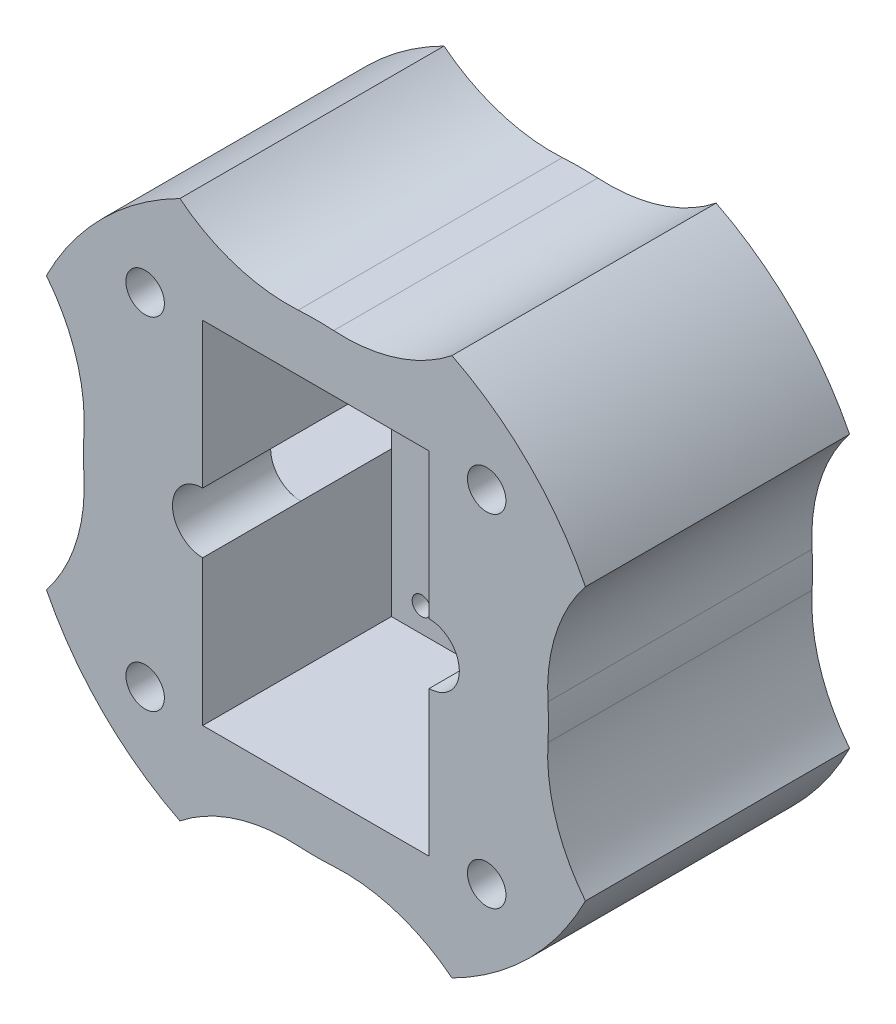
SolidWorks part; units mm, degrees
ref_plane "Front Plane" through (0, 0, 0) normal (0, 0, 1) x (1, 0, 0)
ref_plane "Top Plane" through (0, 0, 0) normal (0, 1, 0) x (1, 0, 0)
ref_plane "Right Plane" through (0, 0, 0) normal (1, 0, 0) x (0, 0, -1)
sketch "Sketch1" plane through (0, 0, 0) normal (0, 0, 1) x (1, 0, 0)
  line L0 (-3.4, 199.25) -> (-3.4, 200.95) construction
  line L9 (3.4, 199.25) -> (3.4, 200.95) construction
  line L10 (-3.4, 199.25) -> (-3.4, 200.95)
  line L11 (3.4, 199.25) -> (3.4, 200.95)
  line L15 (-3.4, 200.95) -> (3.4, 200.95)
  line L16 (-3.4, 199.25) -> (3.4, 199.25)
  arc A0 (11, 243.75) -> (11, 241.25) centre (11, 242.5) ccw construction
  arc A1 (11, 241.25) -> (11, 243.75) centre (11, 242.5) ccw construction
  arc A2 (11, 243.75) -> (11, 241.25) centre (11, 242.5) ccw
  arc A3 (11, 241.25) -> (11, 243.75) centre (11, 242.5) ccw
  arc A4 (-11, 241.25) -> (-11, 243.75) centre (-11, 242.5) ccw construction
  arc A5 (-11, 243.75) -> (-11, 241.25) centre (-11, 242.5) ccw construction
  arc A6 (-11, 241.25) -> (-11, 243.75) centre (-11, 242.5) ccw
  arc A7 (-11, 243.75) -> (-11, 241.25) centre (-11, 242.5) ccw
  arc A8 (11, 201.25) -> (11, 203.75) centre (11, 202.5) ccw construction
  arc A9 (11, 203.75) -> (11, 201.25) centre (11, 202.5) ccw construction
  arc A10 (11, 201.25) -> (11, 203.75) centre (11, 202.5) ccw
  arc A11 (11, 203.75) -> (11, 201.25) centre (11, 202.5) ccw
  arc A12 (-11, 201.25) -> (-11, 203.75) centre (-11, 202.5) ccw construction
  arc A13 (-11, 203.75) -> (-11, 201.25) centre (-11, 202.5) ccw construction
  arc A14 (-11, 201.25) -> (-11, 203.75) centre (-11, 202.5) ccw
  arc A15 (-11, 203.75) -> (-11, 201.25) centre (-11, 202.5) ccw
  circle A17 centre (0, 234.5) radius 6
  circle A18 centre (0, 222.5) radius 40
  dimension "D1" = 80
  dimension "D2" = 12
extrude "Boss-Extrude1" add sketch "Sketch1" along normal blind 10 contours A18 | A10 A11 | L10 L15 L11 L16 | A14 A15 | A17 | A2 A3 | A6 A7
sketch "Sketch3" plane through (0, 0, 10) normal (0, 0, 1) x (1, 0, 0)
  line L1 (15, 245.75) -> (-15, 245.75)
  line L2 (15, 245.75) -> (15, 199.25)
  line L3 (15, 199.25) -> (-15, 199.25)
  line L4 (-15, 245.75) -> (-15, 199.25)
  line L5 (15, 245.75) -> (-15, 199.25) construction
  line L6 (15, 199.25) -> (-15, 245.75) construction
  circle A0 centre (0, 222.5) radius 40 construction
  circle A1 centre (0, 222.5) radius 40
  dimension "D1" = 30
extrude "Boss-Extrude3" add sketch "Sketch3" along normal blind 25
sketch "Sketch4" plane through (0, 0, 35) normal (0, 0, 1) x (1, 0, 0)
  arc A0 (18.0242, 258.209) -> (2.3471, 253.2406) centre (3.6966, 276.2002) cw
  arc A5 (-35.709, 240.5242) -> (-30.7406, 224.8471) centre (-53.7002, 226.1966) cw
  circle A6 centre (0, 222.5) radius 40 construction
  arc A7 (-35.709, 204.4758) -> (-30.7406, 220.1529) centre (-53.7002, 218.8034) ccw
  arc A8 (-35.709, 240.5242) -> (-35.709, 204.4758) centre (0, 222.5) ccw
  arc A9 (35.709, 204.4758) -> (30.7406, 220.1529) centre (53.7002, 218.8034) cw
  arc A10 (35.709, 240.5242) -> (30.7406, 224.8471) centre (53.7002, 226.1966) ccw
  arc A11 (35.709, 204.4758) -> (35.709, 240.5242) centre (0, 222.5) ccw
  arc A12 (30.7406, 220.1529) -> (30.7406, 224.8471) centre (-9.1905, 222.5) ccw
  arc A13 (-30.7406, 220.1529) -> (-30.7406, 224.8471) centre (9.1905, 222.5) cw
  arc A14 (-2.3471, 253.2406) -> (2.3471, 253.2406) centre (0, 213.3095) cw
  arc A15 (-18.0242, 258.209) -> (-2.3471, 253.2406) centre (-3.6966, 276.2002) ccw
  arc A16 (18.0242, 258.209) -> (-18.0242, 258.209) centre (0, 222.5) ccw
  arc A17 (35.709, 204.4758) -> (30.7406, 220.1529) centre (53.7002, 218.8034) cw
  arc A18 (30.7406, 224.8471) -> (30.7406, 220.1529) centre (-9.1905, 222.5) cw
  arc A19 (35.709, 240.5242) -> (30.7406, 224.8471) centre (53.7002, 226.1966) ccw
  arc A20 (35.709, 204.4758) -> (35.709, 240.5242) centre (0, 222.5) ccw
  arc A21 (-18.0242, 186.791) -> (-2.3471, 191.7594) centre (-3.6966, 168.7998) cw
  arc A22 (2.3471, 191.7594) -> (-2.3471, 191.7594) centre (0, 231.6905) cw
  arc A23 (18.0242, 186.791) -> (2.3471, 191.7594) centre (3.6966, 168.7998) ccw
  arc A24 (-18.0242, 186.791) -> (18.0242, 186.791) centre (0, 222.5) ccw
  point P33 (31, 222.5)
  circle M13 centre (0, 222.5) radius 40
  dimension "D4" = 40
  dimension "D5" = 4
extrude "Cut-Extrude1" cut sketch "Sketch4" against normal up to surface (35 mm away) contours A12 A9 A10 M13 | A23 A22 A21 M13 | A16 A15 A14 A0 | A13 A5 A8 A7 up to face at (12.25, 202.5, 0)
sketch "Sketch5" plane through (0, 0, 35) normal (0, 0, 1) x (1, 0, 0)
  line L0 (-15, 222.5) -> (0, 222.5) construction
  line L1 (-15, 245.75) -> (-15, 199.25) construction
  line L2 (0, 222.5) -> (0, 245.75) construction
  line L3 (15, 245.75) -> (-15, 245.75) construction
  line L4 (0, 222.5) -> (-22.6274, 245.1274) construction
  circle A0 centre (-22.6274, 245.1274) radius 2.55
  circle A1 centre (22.6274, 245.1274) radius 2.55
  circle A2 centre (22.6274, 199.8726) radius 2.55
  circle A3 centre (-22.6274, 199.8726) radius 2.55
  dimension "D3" = 5.1
  dimension "D1" = 45
  dimension "D2" = 32
extrude "Cut-Extrude2" cut sketch "Sketch5" against normal blind 5
sketch "Sketch6" plane through (0, 0, 35) normal (0, 0, 1) x (1, 0, 0)
  line L0 (-15, 222.5) -> (15, 222.5) construction
  line L1 (-15, 245.75) -> (-15, 199.25) construction
  line L2 (15, 199.25) -> (15, 245.75) construction
  line L3 (-15, 222.5) -> (-19, 222.5) construction
  line L4 (-15, 245.75) -> (-15, 199.25) construction
  line L5 (-15, 218.5) -> (-15, 226.5)
  line L6 (0, 245.75) -> (0, 199.25) construction
  line L7 (15, 245.75) -> (-15, 245.75) construction
  line L8 (-15, 199.25) -> (15, 199.25) construction
  line L9 (15, 218.5) -> (15, 226.5)
  arc A0 (-15, 218.5) -> (-15, 226.5) centre (-15, 222.5) cw
  arc A1 (15, 218.5) -> (15, 226.5) centre (15, 222.5) ccw
  dimension "D2" = 4
  dimension "D1" = 4
extrude "Cut-Extrude3" cut sketch "Sketch6" against normal up to surface (25 mm away) up to face at (-9.75, 242.5, 10)
sketch "Sketch8" plane through (-15, 0, 0) normal (1, 0, 0) x (0, 0, -1)
  line L2 (-22, 226.5) -> (0, 226.5)
  line L3 (-22, 218.5) -> (0, 218.5)
  line L8 (-22, 218.5) -> (-22, 226.5)
  line L9 (0, 224.8471) -> (0, 240.5242) construction
  line L10 (0, 226.5) -> (0, 218.5)
  line L11 (0, 204.4758) -> (0, 220.1529) construction
extrude "Cut-Extrude4" cut sketch "Sketch8" against normal blind 22 contours L8 L2 L10 L3
